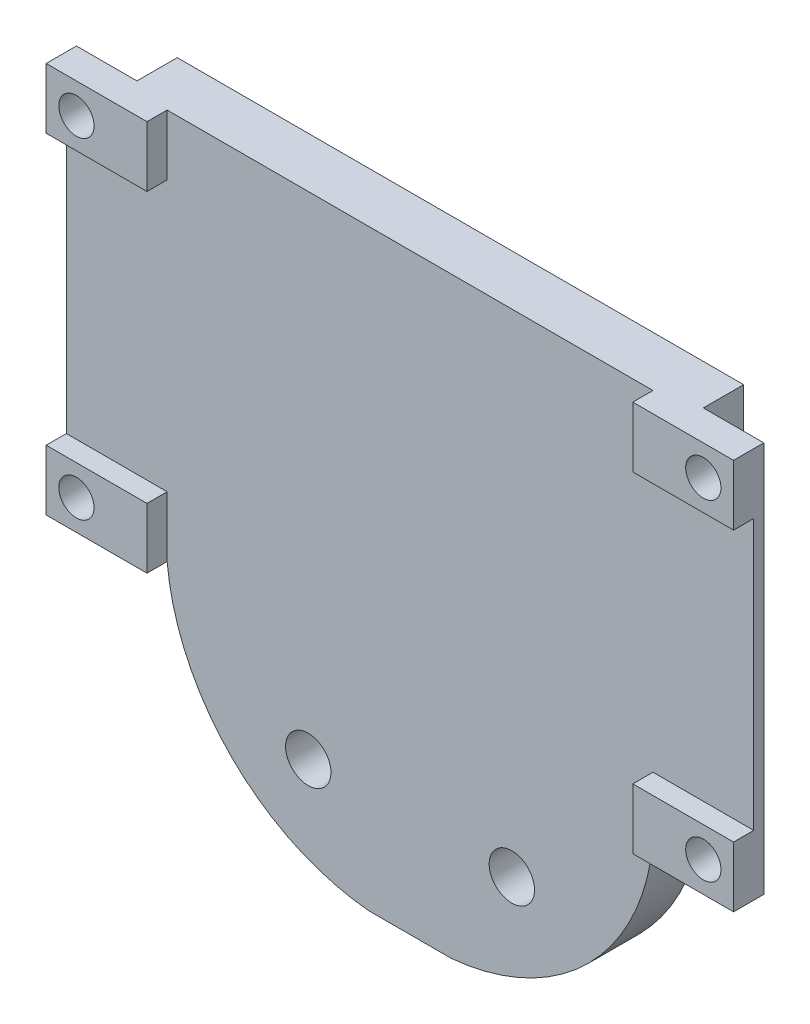
SolidWorks part; units mm, degrees
ref_plane "Plan de face" through (0, 0, 0) normal (0, 0, 1) x (1, 0, 0)
ref_plane "Plan de dessus" through (0, 0, 0) normal (0, 1, 0) x (1, 0, 0)
ref_plane "Plan de droite" through (0, 0, 0) normal (1, 0, 0) x (0, 0, -1)
sketch "Esquisse1" plane through (0, 0, 0) normal (0, 0, 1) x (1, 0, 0)
  line L1 (0, 0) -> (68.2, 0)
  line L2 (0, 0) -> (0, 38.8)
  line L3 (0, 38.8) -> (68.2, 38.8)
  line L4 (68.2, 0) -> (68.2, 38.8)
  dimension "D1" = 68.2
  dimension "D2" = 38.8
extrude "Boss.-Extru.1" add sketch "Esquisse1" along normal blind 1
sketch "Esquisse2" plane through (0, 0, 1) normal (0, 0, 1) x (1, 0, 0)
  line L0 (0, 38.8) -> (6, 38.8)
  line L1 (68.2, 38.8) -> (0, 38.8) construction
  line L2 (6, 38.8) -> (6, 32.8)
  line L3 (6, 32.8) -> (0, 32.8)
  line L4 (0, 38.8) -> (0, 0) construction
  line L5 (0, 32.8) -> (0, 38.8)
  dimension "D1" = 6
  dimension "D2" = 6
sketch "Esquisse3" plane through (0, 0, 1) normal (0, 0, 1) x (1, 0, 0)
  line L0 (68.2, 38.8) -> (62.2, 38.8)
  line L1 (68.2, 38.8) -> (0, 38.8) construction
  line L2 (62.2, 38.8) -> (62.2, 32.8)
  line L3 (62.2, 32.8) -> (68.2, 32.8)
  line L4 (68.2, 0) -> (68.2, 38.8) construction
  line L5 (68.2, 32.8) -> (68.2, 38.8)
  line L6 (68.2, 0) -> (68.2, 6)
  line L7 (68.2, 6) -> (62.2, 6)
  line L8 (62.2, 6) -> (62.2, 0)
  line L9 (0, 0) -> (68.2, 0) construction
  line L10 (62.2, 0) -> (68.2, 0)
  line L11 (0, 0) -> (6, 0)
  line L12 (6, 0) -> (6, 6)
  line L13 (6, 6) -> (0, 6)
  line L14 (0, 38.8) -> (0, 0) construction
  line L15 (0, 6) -> (0, 0)
  dimension "D1" = 6
  dimension "D2" = 6
  dimension "D3" = 6
  dimension "D4" = 6
  dimension "D5" = 6
  dimension "D6" = 6
extrude "Boss.-Extru.2" add sketch "Esquisse3" along normal blind 2
extrude "Boss.-Extru.3" add sketch "Esquisse2" along normal blind 2
sketch "Esquisse5" plane through (0, 0, 1) normal (0, 0, 1) x (1, 0, 0)
  line L0 (6, 38.8) -> (0, 38.8) construction
  line L1 (0, 38.8) -> (0, 32.8) construction
  line L2 (6, 6) -> (0, 6) construction
  line L3 (0, 6) -> (0, 0) construction
  line L4 (68.2, 6) -> (62.2, 6) construction
  line L5 (68.2, 0) -> (68.2, 6) construction
  line L6 (68.2, 32.8) -> (68.2, 38.8) construction
  line L7 (68.2, 38.8) -> (62.2, 38.8) construction
  circle A0 centre (3, 35.8) radius 1.75
  circle A1 centre (3, 3) radius 1.75
  circle A2 centre (65.2, 3) radius 1.75
  circle A3 centre (65.2, 35.8) radius 1.75
  dimension "D1" = 3.5
  dimension "D2" = 3.5
  dimension "D3" = 3.5
  dimension "D4" = 3.5
  dimension "D5" = 3
  dimension "D6" = 3
  dimension "D7" = 3
  dimension "D8" = 3
  dimension "D9" = 3
  dimension "D10" = 3
  dimension "D11" = 3
  dimension "D12" = 3
extrude "Enlèv. mat.-Extru.1" cut sketch "Esquisse5" against normal through all and the other way through all
sketch "Esquisse6" plane through (0, 0, 0) normal (0, 0, -1) x (-1, 0, 0)
  line L1 (-68.2, 38.8) -> (0, 38.8)
  line L2 (-68.2, 38.8) -> (-68.2, 0)
  line L3 (-68.2, 0) -> (0, 0)
  line L4 (0, 38.8) -> (0, 0)
  line L5 (0, 38.8) -> (-10, 38.8)
  line L6 (0, 38.8) -> (0, 32.8)
  line L7 (0, 32.8) -> (-10, 32.8)
  line L8 (-10, 38.8) -> (-10, 32.8)
  line L9 (-68.2, 38.8) -> (-58.2, 38.8)
  line L10 (-68.2, 38.8) -> (-68.2, 32.8)
  line L11 (-68.2, 32.8) -> (-58.2, 32.8)
  line L12 (-58.2, 38.8) -> (-58.2, 32.8)
  line L13 (-68.2, 0) -> (-58.2, 0)
  line L14 (-68.2, 0) -> (-68.2, 6)
  line L15 (-68.2, 6) -> (-58.2, 6)
  line L16 (-58.2, 0) -> (-58.2, 6)
  line L17 (0, 0) -> (-10, 0)
  line L18 (0, 0) -> (0, 6)
  line L19 (0, 6) -> (-10, 6)
  line L20 (-10, 0) -> (-10, 6)
  circle A0 centre (-65.2, 35.8) radius 1.8692
  circle A1 centre (-65.2, 3) radius 1.75
  circle A2 centre (-3, 3) radius 1.75
  circle A3 centre (-3, 35.8) radius 1.75
  circle M16 centre (-65.2, 3) radius 1.75
  circle M17 centre (-3, 3) radius 1.75
  circle M18 centre (-3, 35.8) radius 1.75
  line M19 (0, 0) -> (0, 38.8)
  line M20 (0, 38.8) -> (-68.2, 38.8)
  line M21 (-68.2, 38.8) -> (-68.2, 0)
  line M22 (-68.2, 0) -> (0, 0)
  dimension "D1" = 6
  dimension "D2" = 10
  dimension "D3" = 10
  dimension "D4" = 6
  dimension "D5" = 6
  dimension "D6" = 10
  dimension "D7" = 10
  dimension "D8" = 6
extrude "Boss.-Extru.4" add sketch "Esquisse6" against normal blind 3 contours L16 L15 M22 M21 M16 | L12 L11 A0 M20 M21 | L20 L19 M22 M19 M17 | L8 L7 L4 M20 M18
sketch "Esquisse7" plane through (0, 0, 0) normal (0, 0, -1) x (-1, 0, 0)
  line L0 (-68.2, 38.8) -> (0, 38.8) construction
  line L1 (-62.2, 38.8) -> (-6, 38.8)
  line L2 (-62.2, 38.8) -> (-62.2, 0)
  line L3 (-62.2, 0) -> (-6, 0)
  line L4 (-6, 38.8) -> (-6, 0)
  line L5 (0, 0) -> (-68.2, 0) construction
  line L6 (-68.2, 0) -> (-68.2, 38.8) construction
  line L7 (0, 38.8) -> (0, 0) construction
  dimension "D1" = 6
  dimension "D2" = 6
extrude "Boss.-Extru.5" add sketch "Esquisse7" along normal blind 4
sketch "Esquisse8" plane through (0, 0, 0) normal (0, -1, 0) x (1, 0, 0)
  line L0 (62.2, -4) -> (6, -4) construction
  line L1 (10, 1) -> (58.2, 1)
  line L2 (10, 1) -> (10, -4)
  line L3 (10, -4) -> (58.2, -4)
  line L4 (58.2, 1) -> (58.2, -4)
  line L5 (62.2, -4) -> (62.2, 0) construction
  dimension "D1" = 4
extrude "Boss.-Extru.6" add sketch "Esquisse8" along normal blind 20 contours L2 L1 L4 L3
sketch "Esquisse9" plane through (0, 0, 1) normal (0, 0, 1) x (1, 0, 0)
  line L1 (10, -20) -> (58.2, -20)
  line L2 (10, -20) -> (10, 0)
  line L3 (10, 0) -> (58.2, 0)
  line L4 (58.2, -20) -> (58.2, 0)
  circle A0 centre (24, -10) radius 2.25
  circle A1 centre (44.2, -10) radius 2.25
  arc A2 (10, 0) -> (34.1, -20) centre (32.05, 2.05) ccw
  arc A3 (58.2, 0) -> (34.1, -20) centre (36.15, 2.05) cw
  line M10 (10, 0) -> (10, -20)
  line M11 (10, -20) -> (58.2, -20)
  line M12 (58.2, -20) -> (58.2, 0)
  dimension "D1" = 4.5
  dimension "D2" = 4.5
  dimension "D3" = 14
  dimension "D4" = 14
extrude "Enlèv. mat.-Extru.2" cut sketch "Esquisse9" against normal blind 20 contours A2 M10 M11 | A0 | A1 | A3 L1 M12
